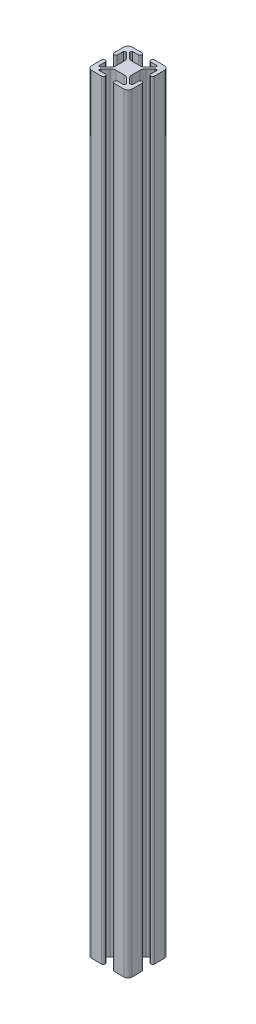
SolidWorks part; units mm, degrees
ref_plane "前视基准面" through (0, 0, 0) normal (0, 0, 1) x (1, 0, 0)
ref_plane "上视基准面" through (0, 0, 0) normal (0, 1, 0) x (1, 0, 0)
ref_plane "右视基准面" through (0, 0, 0) normal (1, 0, 0) x (0, 0, -1)
sketch "草图2" plane through (0, 0, 0) normal (0, 1, 0) x (1, 0, 0)
  line L0 (-1.0428, -10.0859) -> (3.8572, -10.0859)
  line L1 (1.0762, -11.8859) -> (3.8572, -11.8859)
  line L2 (2.8854, -15.3072) -> (0.7226, -13.1443)
  line L3 (2.1786, -16.0141) -> (0.0157, -13.8512)
  line L4 (-3.0428, -12.0859) -> (-3.0428, -16.9859)
  line L5 (-1.2428, -14.2048) -> (-1.2428, -16.9859)
  line L6 (-0.7428, -13.7048) -> (-0.3378, -13.7048)
  line L7 (0.5762, -12.3859) -> (0.5762, -12.7908)
  line L8 (-1.0428, -30.0859) -> (3.8572, -30.0859)
  line L9 (1.0762, -28.2859) -> (3.8572, -28.2859)
  line L10 (2.8854, -24.8645) -> (0.7226, -27.0274)
  line L11 (2.1786, -24.1577) -> (0.0157, -26.3205)
  line L12 (-3.0428, -28.0859) -> (-3.0428, -23.1859)
  line L13 (-1.2428, -25.9669) -> (-1.2428, -23.1859)
  line L14 (-0.7428, -26.4669) -> (-0.3378, -26.4669)
  line L15 (0.5762, -27.7859) -> (0.5762, -27.3809)
  line L16 (14.9572, -10.0859) -> (10.0572, -10.0859)
  line L17 (12.8383, -11.8859) -> (10.0572, -11.8859)
  line L18 (11.029, -15.3072) -> (13.1919, -13.1443)
  line L19 (11.7359, -16.0141) -> (13.8988, -13.8512)
  line L20 (16.9572, -12.0859) -> (16.9572, -16.9859)
  line L21 (15.1572, -14.2048) -> (15.1572, -16.9859)
  line L22 (14.6572, -13.7048) -> (14.2523, -13.7048)
  line L23 (13.3383, -12.3859) -> (13.3383, -12.7908)
  line L24 (14.9572, -30.0859) -> (10.0572, -30.0859)
  line L25 (12.8383, -28.2859) -> (10.0572, -28.2859)
  line L26 (11.029, -24.8645) -> (13.1919, -27.0274)
  line L27 (11.7359, -24.1577) -> (13.8988, -26.3205)
  line L28 (16.9572, -28.0859) -> (16.9572, -23.1859)
  line L29 (15.1572, -25.9669) -> (15.1572, -23.1859)
  line L30 (14.6572, -26.4669) -> (14.2523, -26.4669)
  line L31 (13.3383, -27.7859) -> (13.3383, -27.3809)
  line L32 (5.0068, -16.1859) -> (8.9077, -16.1859)
  line L33 (10.8572, -18.1354) -> (10.8572, -22.0363)
  line L34 (3.0572, -18.1354) -> (3.0572, -22.0363)
  line L35 (5.0068, -23.9859) -> (8.9077, -23.9859)
  circle A0 centre (6.9572, -20.0859) radius 2.5
  arc A1 (2.8854, -15.3072) -> (5.0068, -16.1859) centre (5.0068, -13.1859) ccw
  arc A2 (3.0572, -18.1354) -> (2.1786, -16.0141) centre (0.0572, -18.1354) ccw
  arc A3 (3.8572, -11.8859) -> (3.8572, -10.0859) centre (3.8572, -10.9859) ccw
  arc A4 (0.5762, -12.7908) -> (0.7226, -13.1443) centre (1.0762, -12.7908) ccw
  arc A5 (0.0157, -13.8512) -> (-0.3378, -13.7048) centre (-0.3378, -14.2048) ccw
  arc A6 (-3.0428, -16.9859) -> (-1.2428, -16.9859) centre (-2.1428, -16.9859) ccw
  arc A7 (-1.0428, -10.0859) -> (-3.0428, -12.0859) centre (-1.0428, -12.0859) ccw
  arc A8 (-0.7428, -13.7048) -> (-1.2428, -14.2048) centre (-0.7428, -14.2048) ccw
  arc A9 (1.0762, -11.8859) -> (0.5762, -12.3859) centre (1.0762, -12.3859) ccw
  arc A10 (5.0068, -23.9859) -> (2.8854, -24.8645) centre (5.0068, -26.9859) ccw
  arc A11 (2.1786, -24.1577) -> (3.0572, -22.0363) centre (0.0572, -22.0363) ccw
  arc A12 (3.8572, -30.0859) -> (3.8572, -28.2859) centre (3.8572, -29.1859) ccw
  arc A13 (0.7226, -27.0274) -> (0.5762, -27.3809) centre (1.0762, -27.3809) ccw
  arc A14 (-0.3378, -26.4669) -> (0.0157, -26.3205) centre (-0.3378, -25.9669) ccw
  arc A15 (-1.2428, -23.1859) -> (-3.0428, -23.1859) centre (-2.1428, -23.1859) ccw
  arc A16 (-3.0428, -28.0859) -> (-1.0428, -30.0859) centre (-1.0428, -28.0859) ccw
  arc A17 (-1.2428, -25.9669) -> (-0.7428, -26.4669) centre (-0.7428, -25.9669) ccw
  arc A18 (0.5762, -27.7859) -> (1.0762, -28.2859) centre (1.0762, -27.7859) ccw
  arc A19 (8.9077, -16.1859) -> (11.029, -15.3072) centre (8.9077, -13.1859) ccw
  arc A20 (11.7359, -16.0141) -> (10.8572, -18.1354) centre (13.8572, -18.1354) ccw
  arc A21 (10.0572, -10.0859) -> (10.0572, -11.8859) centre (10.0572, -10.9859) ccw
  arc A22 (13.1919, -13.1443) -> (13.3383, -12.7908) centre (12.8383, -12.7908) ccw
  arc A23 (14.2523, -13.7048) -> (13.8988, -13.8512) centre (14.2523, -14.2048) ccw
  arc A24 (15.1572, -16.9859) -> (16.9572, -16.9859) centre (16.0572, -16.9859) ccw
  arc A25 (16.9572, -12.0859) -> (14.9572, -10.0859) centre (14.9572, -12.0859) ccw
  arc A26 (15.1572, -14.2048) -> (14.6572, -13.7048) centre (14.6572, -14.2048) ccw
  arc A27 (13.3383, -12.3859) -> (12.8383, -11.8859) centre (12.8383, -12.3859) ccw
  arc A28 (11.029, -24.8645) -> (8.9077, -23.9859) centre (8.9077, -26.9859) ccw
  arc A29 (10.8572, -22.0363) -> (11.7359, -24.1577) centre (13.8572, -22.0363) ccw
  arc A30 (10.0572, -28.2859) -> (10.0572, -30.0859) centre (10.0572, -29.1859) ccw
  arc A31 (13.3383, -27.3809) -> (13.1919, -27.0274) centre (12.8383, -27.3809) ccw
  arc A32 (13.8988, -26.3205) -> (14.2523, -26.4669) centre (14.2523, -25.9669) ccw
  arc A33 (16.9572, -23.1859) -> (15.1572, -23.1859) centre (16.0572, -23.1859) ccw
  arc A34 (14.9572, -30.0859) -> (16.9572, -28.0859) centre (14.9572, -28.0859) ccw
  arc A35 (14.6572, -26.4669) -> (15.1572, -25.9669) centre (14.6572, -25.9669) ccw
  arc A36 (12.8383, -28.2859) -> (13.3383, -27.7859) centre (12.8383, -27.7859) ccw
extrude "凸台-拉伸1" add sketch "草图2" along normal blind 380 contours L18 A22 L23 A27 L17 A21 L16 A25 L20 A24 L21 A26 L22 A23 L19 A20 L33 A29 L27 A32 L30 A35 L29 A33 L28 A34 L24 A30 L25 A36 L31 A31 L26 A28 L35 A10 L10 A13 L15 A18 L9 A12 L8 A16 L12 A15 L13 A17 L14 A14 L11 A11 L34 A2 L3 A5 L6 A8 L5 A6 L4 A7 L0 A3 L1 A9 L7 A4 L2 A1 L32 A19
